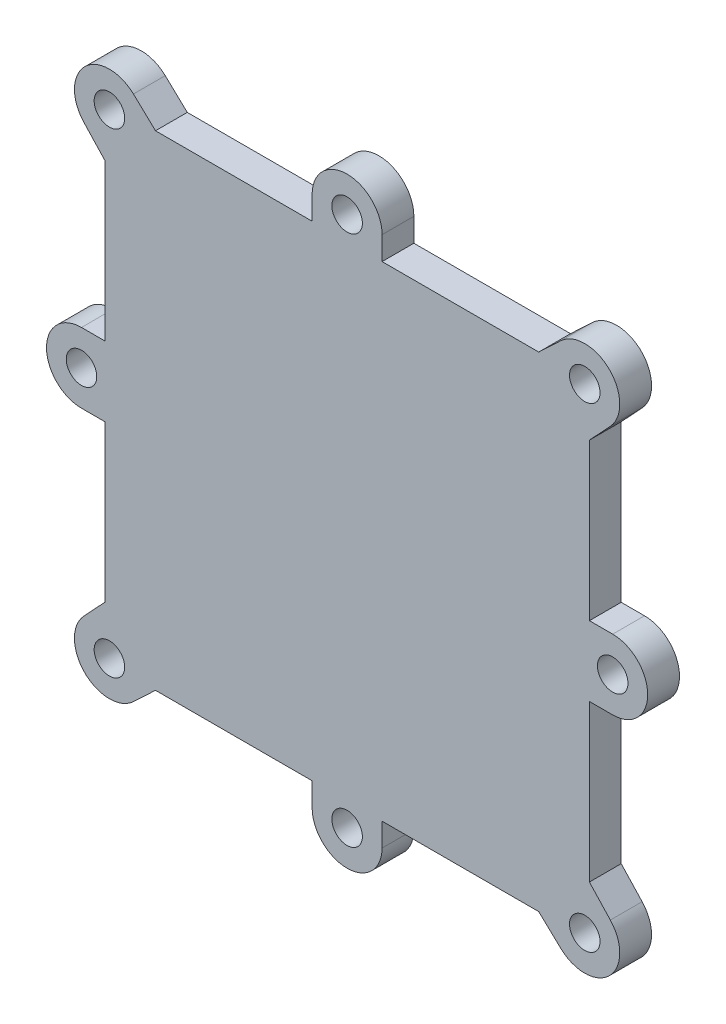
SolidWorks part; units mm, degrees
material "Custom Plastic"
ref_plane "X-Y Datum" through (0, 0, 0) normal (0, 0, 1) x (1, 0, 0)
ref_plane "X-Z Datum" through (0, 0, 0) normal (0, 1, 0) x (1, 0, 0)
ref_plane "Y-Z Datum" through (0, 0, 0) normal (1, 0, 0) x (0, 0, -1)
sketch "Sketch1" plane through (0, 0, 0) normal (0, 0, 1) x (1, 0, 0)
  line L1 (-38.1, 38.1) -> (38.1, 38.1)
  line L2 (-38.1, 38.1) -> (-38.1, -38.1)
  line L3 (-38.1, -38.1) -> (38.1, -38.1)
  line L4 (38.1, 38.1) -> (38.1, -38.1)
  line L5 (-38.1, 38.1) -> (38.1, -38.1) construction
  line L6 (-38.1, -38.1) -> (38.1, 38.1) construction
  point P0 (0, 0)
  dimension "D1" = 76.2
  dimension "D2" = 76.2
extrude "Boss-Extrude1" add sketch "Sketch1" along normal blind 5
fillet "Fillet1" radius 5.334 4 edges at (-38.1, -38.1, 2.5) (38.1, -38.1, 2.5) (38.1, 38.1, 2.5) (-38.1, 38.1, 2.5)
sketch "Sketch2" plane through (0, 0, 5) normal (0, 0, 1) x (1, 0, 0)
  line L24 (-38.1, 30.0901) -> (-38.1, 5.5)
  line L25 (-38.1, 5.5) -> (-41.7647, 5.5)
  line L26 (-41.7647, -5.5) -> (-38.1, -5.5)
  line L27 (-38.1, -5.5) -> (-38.1, -30.0901)
  line L28 (-38.1, -30.0901) -> (-41.394, -33.6205)
  line L29 (-38.1, -30.0901) -> (-41.394, -33.6205)
  line L30 (-30.1318, -38.1) -> (-5.5, -38.1)
  line L31 (-5.5, -38.1) -> (-5.5, -41.7647)
  line L32 (5.5, -41.7647) -> (5.5, -38.1)
  line L33 (5.5, -38.1) -> (30.1318, -38.1)
  line L34 (-33.5966, -41.3716) -> (-30.1318, -38.1)
  line L35 (-33.5966, -41.3716) -> (-30.1318, -38.1)
  line L36 (38.1, -30.0901) -> (38.1, -5.5)
  line L37 (38.1, -5.5) -> (41.7647, -5.5)
  line L38 (41.7647, 5.5) -> (38.1, 5.5)
  line L39 (38.1, 5.5) -> (38.1, 30.0901)
  line L40 (30.1318, -38.1) -> (33.5966, -41.3716)
  line L41 (30.1318, -38.1) -> (33.5966, -41.3716)
  line L42 (30.1318, 38.1) -> (5.5, 38.1)
  line L43 (5.5, 38.1) -> (5.5, 41.7647)
  line L44 (-5.5, 41.7647) -> (-5.5, 38.1)
  line L45 (-5.5, 38.1) -> (-30.1318, 38.1)
  line L46 (41.394, -33.6205) -> (38.1, -30.0901)
  line L47 (41.394, -33.6205) -> (38.1, -30.0901)
  line L48 (-38.1, 30.0901) -> (-38.1, 5.5)
  line L49 (-38.1, 5.5) -> (-41.7647, 5.5)
  line L50 (-41.7647, -5.5) -> (-38.1, -5.5)
  line L51 (-38.1, -5.5) -> (-38.1, -30.0901)
  line L54 (-30.1318, -38.1) -> (-5.5, -38.1)
  line L55 (-5.5, -38.1) -> (-5.5, -41.7647)
  line L56 (5.5, -41.7647) -> (5.5, -38.1)
  line L57 (5.5, -38.1) -> (30.1318, -38.1)
  line L60 (38.1, -30.0901) -> (38.1, -5.5)
  line L61 (38.1, -5.5) -> (41.7647, -5.5)
  line L62 (41.7647, 5.5) -> (38.1, 5.5)
  line L63 (38.1, 5.5) -> (38.1, 30.0901)
  line L66 (30.1318, 38.1) -> (5.5, 38.1)
  line L67 (5.5, 38.1) -> (5.5, 41.7647)
  line L68 (-5.5, 41.7647) -> (-5.5, 38.1)
  line L69 (-5.5, 38.1) -> (-30.1318, 38.1)
  line L238 (38.1, 30.0901) -> (41.394, 33.6205)
  line L239 (38.1, 30.0901) -> (41.394, 33.6205)
  line L240 (33.5966, 41.3716) -> (30.1318, 38.1)
  line L241 (33.5966, 41.3716) -> (30.1318, 38.1)
  line L242 (-30.1318, 38.1) -> (-33.5966, 41.3716)
  line L243 (-30.1318, 38.1) -> (-33.5966, 41.3716)
  line L244 (-41.394, 33.6205) -> (-38.1, 30.0901)
  line L245 (-41.394, 33.6205) -> (-38.1, 30.0901)
  arc A8 (-41.7647, 5.5) -> (-41.7647, -5.5) centre (-41.7647, 0) ccw
  arc A9 (-41.394, -33.6205) -> (-33.5966, -41.3716) centre (-37.3726, -37.3726) ccw
  arc A10 (-5.5, -41.7647) -> (5.5, -41.7647) centre (0, -41.7647) ccw
  arc A11 (33.5966, -41.3716) -> (41.394, -33.6205) centre (37.3726, -37.3726) ccw
  arc A12 (41.7647, -5.5) -> (41.7647, 5.5) centre (41.7647, 0) ccw
  arc A13 (41.394, 33.6205) -> (33.5966, 41.3716) centre (37.3726, 37.3726) ccw
  arc A14 (5.5, 41.7647) -> (-5.5, 41.7647) centre (0, 41.7647) ccw
  arc A15 (-33.5966, 41.3716) -> (-41.394, 33.6205) centre (-37.3726, 37.3726) ccw
  arc A16 (-41.7647, 5.5) -> (-41.7647, -5.5) centre (-41.7647, 0) ccw
  arc A17 (-41.394, -33.6205) -> (-33.5966, -41.3716) centre (-37.3726, -37.3726) ccw
  arc A18 (-5.5, -41.7647) -> (5.5, -41.7647) centre (0, -41.7647) ccw
  arc A19 (33.5966, -41.3716) -> (41.394, -33.6205) centre (37.3726, -37.3726) ccw
  arc A20 (41.7647, -5.5) -> (41.7647, 5.5) centre (41.7647, 0) ccw
  arc A21 (41.394, 33.6205) -> (33.5966, 41.3716) centre (37.3726, 37.3726) ccw
  arc A22 (5.5, 41.7647) -> (-5.5, 41.7647) centre (0, 41.7647) ccw
  arc A23 (-33.5966, 41.3716) -> (-41.394, 33.6205) centre (-37.3726, 37.3726) ccw
  dimension "D1" = 0
extrude "Boss-Extrude2" add sketch "Sketch2" against normal blind 5
hole_wizard "M4 Clearance Hole1" positions "Sketch3" profile "Sketch4" hole size "M4" standard "ANSI Metric" end condition through all
sketch "Sketch3" plane through (0, 0, 5) normal (0, 0, 1) x (1, 0, 0)
  point P0 (0, -41.7647)
  point P3 (37.3726, -37.3726)
  point P6 (-37.3726, -37.3726)
  point P9 (-41.7647, 0)
  point P12 (41.7647, 0)
  point P15 (37.3726, 37.3726)
  point P18 (0, 41.7647)
  point P21 (-37.3726, 37.3726)
sketch "Sketch4" plane through (0, -41.7647, 5) normal (1, 0, 0) x (0, -1, 0)
  line L0 (0, 0) -> (0, 5)
  line L1 (0, 5) -> (2.4, 5)
  line L2 (2.4, 5) -> (2.4, 0)
  line L5 (2.4, 0) -> (0, 0)
  line L11 (0, -6.35) -> (0, 107.95) construction
  dimension "Thru Hole Dia." = 4.8
  dimension "Thru Hole Depth" = 5
